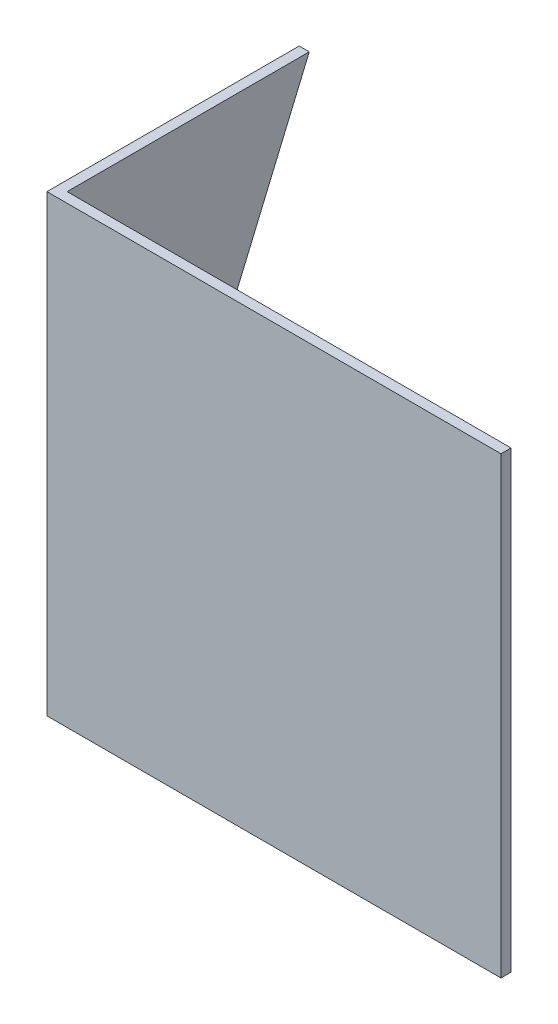
SolidWorks part; units mm, degrees
ref_plane "Front Plane" through (0, 0, 0) normal (0, 0, 1) x (1, 0, 0)
ref_plane "Top Plane" through (0, 0, 0) normal (0, 1, 0) x (1, 0, 0)
ref_plane "Right Plane" through (0, 0, 0) normal (1, 0, 0) x (0, 0, -1)
sketch "Sketch1" plane through (0, 0, 0) normal (0, 1, 0) x (1, 0, 0)
  line L1 (-18.4037, 33.1674) -> (-16.4037, 33.1674)
  line L2 (-18.4037, 33.1674) -> (-18.4037, -16.8326)
  line L3 (-18.4037, -16.8326) -> (-16.4037, -16.8326)
  line L4 (-16.4037, 33.1674) -> (-16.4037, -16.8326)
  line L5 (71.5963, -16.8326) -> (-18.4037, -16.8326)
  line L6 (71.5963, -16.8326) -> (71.5963, -14.8326)
  line L7 (71.5963, -14.8326) -> (-18.4037, -14.8326)
  line L8 (-18.4037, -16.8326) -> (-18.4037, -14.8326)
  dimension "D1" = 2
  dimension "D2" = 2
  dimension "D3" = 90
  dimension "D4" = 50
extrude "Boss-Extrude1" add sketch "Sketch1" along normal blind 90 contours L3 L4 L1 L2 | L5 L6 L7 L8
sketch "Sketch2" plane through (-18.4037, 0, 0) normal (-1, 0, 0) x (0, 0, 1)
  line L0 (-33.1674, 90) -> (5.0354, 0)
  line L1 (-33.1674, 0) -> (16.8326, 0) construction
  line L2 (-33.1674, 90) -> (-33.1674, 0) construction
  line L3 (-33.1674, 90) -> (-33.1674, 0)
  line L4 (-33.1674, 0) -> (5.0354, 0)
  dimension "D1" = 23
extrude "Cut-Extrude1" cut sketch "Sketch2" against normal up to next
